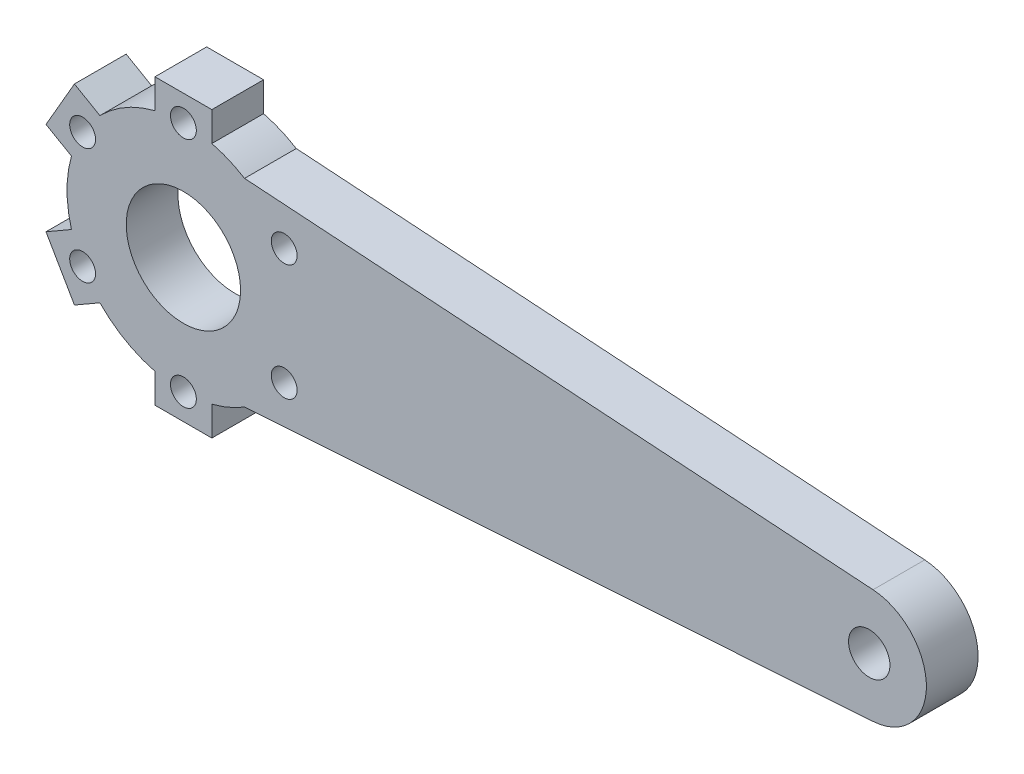
SolidWorks part; units mm, degrees
ref_plane "前视基准面" through (0, 0, 0) normal (0, 0, 1) x (1, 0, 0)
ref_plane "上视基准面" through (0, 0, 0) normal (0, 1, 0) x (1, 0, 0)
ref_plane "右视基准面" through (0, 0, 0) normal (1, 0, 0) x (0, 0, -1)
sketch "草图1" plane through (0, 0, 0) normal (0, 0, 1) x (1, 0, 0)
  line L0 (0, 0) -> (11.05, 0) construction
  line L3 (1.326, 19.8458) -> (133.3367, 11.0254)
  line L4 (1.326, -19.8458) -> (133.3367, -11.0254)
  line L5 (132.6, 0) -> (0, 0) construction
  line L6 (0, 0) -> (0, 32.9628) construction
  line L7 (0, 0) -> (-8.3779, 36.2886) construction
  line L8 (5.5, 27.5) -> (-5.5, 27.5)
  line L9 (-5.5, 27.5) -> (-5.5, 21.8174)
  line L10 (5.5, 27.5) -> (5.5, 21.8174)
  line L11 (-26.5657, 8.9869) -> (-21.6444, 6.1456)
  line L12 (-21.0657, 18.5131) -> (-26.5657, 8.9869)
  line L13 (-21.0657, 18.5131) -> (-16.1444, 15.6719)
  line L14 (-21.0657, -18.5131) -> (-16.1444, -15.6719)
  line L15 (-26.5657, -8.9869) -> (-21.0657, -18.5131)
  line L16 (-26.5657, -8.9869) -> (-21.6444, -6.1456)
  line L17 (5.5, -27.5) -> (5.5, -21.8174)
  line L18 (-5.5, -27.5) -> (5.5, -27.5)
  line L19 (-5.5, -27.5) -> (-5.5, -21.8174)
  circle A0 centre (0, 0) radius 11.05
  arc A3 (1.326, 19.8458) -> (1.326, -19.8458) centre (0, 0) ccw
  arc A4 (133.3367, -11.0254) -> (133.3367, 11.0254) centre (132.6, 0) ccw
  circle A5 centre (0, 0) radius 22.5
  circle A6 centre (0, 22.5) radius 2.5
  circle A7 centre (19.4856, 11.25) radius 2.5
  circle A8 centre (19.4856, -11.25) radius 2.5
  circle A9 centre (0, -22.5) radius 2.5
  circle A10 centre (-19.4856, -11.25) radius 2.5
  circle A11 centre (-19.4856, 11.25) radius 2.5
  circle A12 centre (132.6, 0) radius 4
  point P27 (0, 0)
  point P31 (0, 27.5)
  point P45 (0, 0)
  dimension "D1" = 22.1
  dimension "D2" = 45
  dimension "D3" = 5
  dimension "D8" = 8
  dimension "D5" = 5.5
  dimension "D6" = 5
  dimension "D4" = 6
  dimension "D7" = 4
extrude "凸台-拉伸1" add sketch "草图1" along normal blind 10 contours A8 A5 L4 A4 L3 A7 | A8 A5 A7 L3 A3 L4 A0 | A11 A5 A10 A9 L4 A3 L3 A6 | A6 A5 L10 L8 L9 | A11 A5 L13 L12 L11 | A10 A5 L16 L15 L14 | A9 A5 L19 L18 L17
